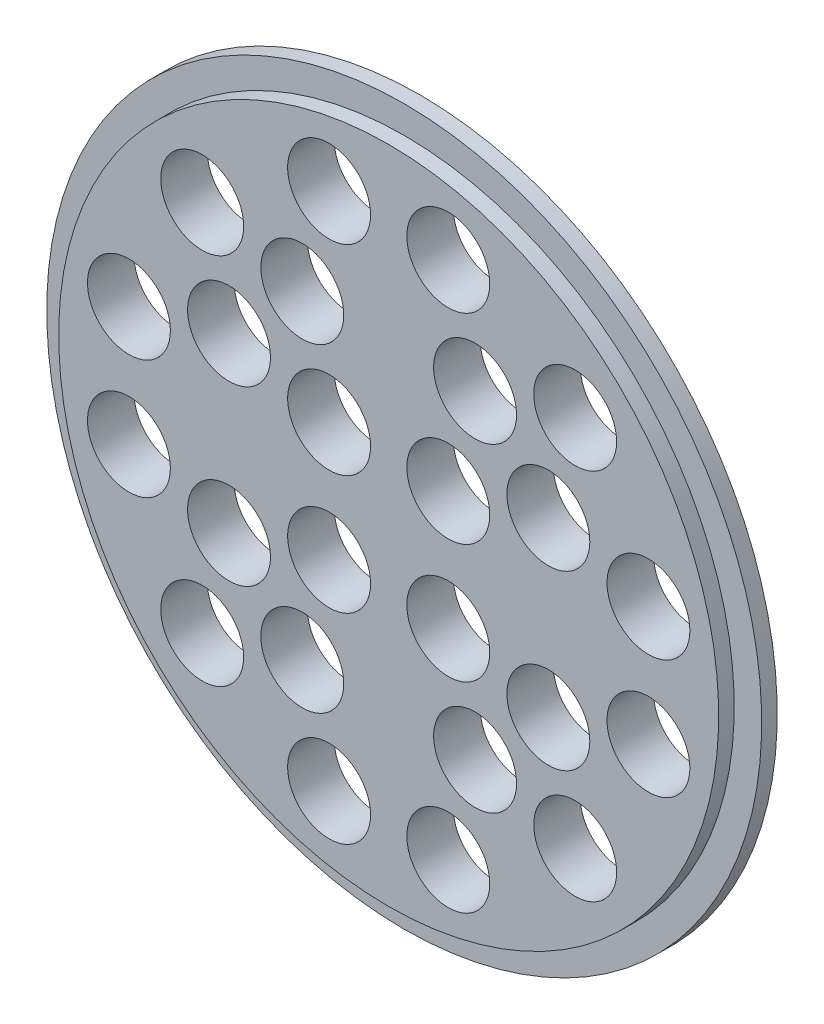
SolidWorks part; units mm, degrees
material "PET"
ref_plane "Front Plane" through (0, 0, 0) normal (0, 0, 1) x (1, 0, 0)
ref_plane "Top Plane" through (0, 0, 0) normal (0, 1, 0) x (1, 0, 0)
ref_plane "Right Plane" through (0, 0, 0) normal (1, 0, 0) x (0, 0, -1)
sketch "Sketch1" plane through (0, 0, 0) normal (0, 0, 1) x (1, 0, 0)
  line L0 (0, 0) -> (-34.5, 0) construction
  line L1 (0, 0) -> (34.5, 0) construction
  line L2 (0, 0) -> (0, -34.5) construction
  line L3 (0, 0) -> (0, 34.5) construction
  line L4 (17.9974, 17.9974) -> (15.4093, 8.3382) construction
  line L5 (15.4093, 8.3382) -> (5.75, 5.75) construction
  line L6 (5.75, 5.75) -> (8.3382, 15.4093) construction
  line L7 (8.3382, 15.4093) -> (17.9974, 17.9974) construction
  line L8 (0, 0) -> (5.75, 5.75) construction
  line L9 (0, 0) -> (5.75, -5.75) construction
  line L10 (8.3382, 15.4093) -> (15.4093, 8.3382) construction
  line L11 (15.4093, 8.3382) -> (25.0685, 5.75) construction
  line L12 (5.75, 25.0685) -> (8.3382, 15.4093) construction
  circle A0 centre (0, 0) radius 34.5
  circle A1 centre (5.75, 5.75) radius 4
  circle A2 centre (8.3382, 15.4093) radius 4
  circle A3 centre (17.9974, 17.9974) radius 4
  circle A4 centre (15.4093, 8.3382) radius 4
  circle A5 centre (25.0685, 5.75) radius 4
  circle A6 centre (5.75, 25.0685) radius 4
  circle A7 centre (25.0686, -5.75) radius 4
  circle A8 centre (15.4093, -8.3382) radius 4
  circle A9 centre (17.9975, -17.9974) radius 4
  circle A10 centre (8.3382, -15.4092) radius 4
  circle A11 centre (5.75, -25.0685) radius 4
  circle A12 centre (5.75, -5.75) radius 4
  circle A13 centre (-5.7499, -25.0685) radius 4
  circle A14 centre (-8.3381, -15.4093) radius 4
  circle A15 centre (-17.9974, -17.9974) radius 4
  circle A16 centre (-15.4092, -8.3382) radius 4
  circle A17 centre (-25.0684, -5.75) radius 4
  circle A18 centre (-5.7499, -5.75) radius 4
  circle A19 centre (-25.0685, 5.75) radius 4
  circle A20 centre (-15.4092, 8.3382) radius 4
  circle A21 centre (-17.9974, 17.9974) radius 4
  circle A22 centre (-8.3382, 15.4092) radius 4
  circle A23 centre (-5.75, 25.0685) radius 4
  circle A24 centre (-5.75, 5.75) radius 4
  dimension "D1" = 69
  dimension "D2" = 8
  dimension "D3" = 5.75
  dimension "D4" = 5.75
  dimension "D5" = 5.75
  dimension "D6" = 150
  dimension "D7" = 5.75
  dimension "D8" = 10
  dimension "D13" = 90
  dimension "D14" = 8.1317
  dimension "D12" = 4
extrude "Boss-Extrude1" add sketch "Sketch1" along normal blind 4.5
sketch "Sketch2" plane through (0, 0, 0) normal (1, 0, 0) x (0, 0, -1)
  line L1 (0, 34.5) -> (-1.5, 34.5)
  line L2 (0, 34.5) -> (0, 31.85)
  line L3 (0, 31.85) -> (-1.5, 31.85)
  line L4 (-1.5, 34.5) -> (-1.5, 31.85)
  line L5 (-4.5, 34.5) -> (-3, 34.5)
  line L6 (-4.5, 34.5) -> (-4.5, 31.85)
  line L7 (-4.5, 31.85) -> (-3, 31.85)
  line L8 (-3, 34.5) -> (-3, 31.85)
  dimension "D1" = 2.65
  dimension "D2" = 1.5
sketch "Sketch3" plane through (0, 0, 0) normal (1, 0, 0) x (0, 0, -1)
  line L0 (0, 0) -> (-4.5, 0) construction
revolve "Cut-Revolve1" cut sketch "Sketch2" angle 360 about L0
sketch "Sketch4" plane through (0, 0, 0) normal (0, 1, 0) x (1, 0, 0)
  line L0 (31.85, 0) -> (-31.85, 0) construction
  line L1 (-0.775, 0) -> (0.775, 0)
  line L2 (-0.775, 0) -> (-0.775, -1.5)
  line L3 (-0.775, -1.5) -> (0.775, -1.5)
  line L4 (0.775, 0) -> (0.775, -1.5)
  line L5 (0, 200000) -> (0, -200004.5) construction
  dimension "D1" = 1.55
  dimension "D2" = 0.775
  dimension "D3" = 1.5
extrude "Cut-Extrude1" cut sketch "Sketch4" against normal through all both and the other way through all
sketch "Sketch5" plane through (0, 0, 0) normal (1, 0, 0) x (0, 0, -1)
  line L0 (0, -31.8406) -> (0, 31.8406) construction
  line L1 (0, 0.775) -> (-1.5, 0.775)
  line L2 (0, 0.775) -> (0, -0.775)
  line L3 (0, -0.775) -> (-1.5, -0.775)
  line L4 (-1.5, 0.775) -> (-1.5, -0.775)
  dimension "D1" = 1.5
  dimension "D2" = 1.55
  dimension "D3" = 0.775
extrude "Cut-Extrude2" cut sketch "Sketch5" against normal through all
